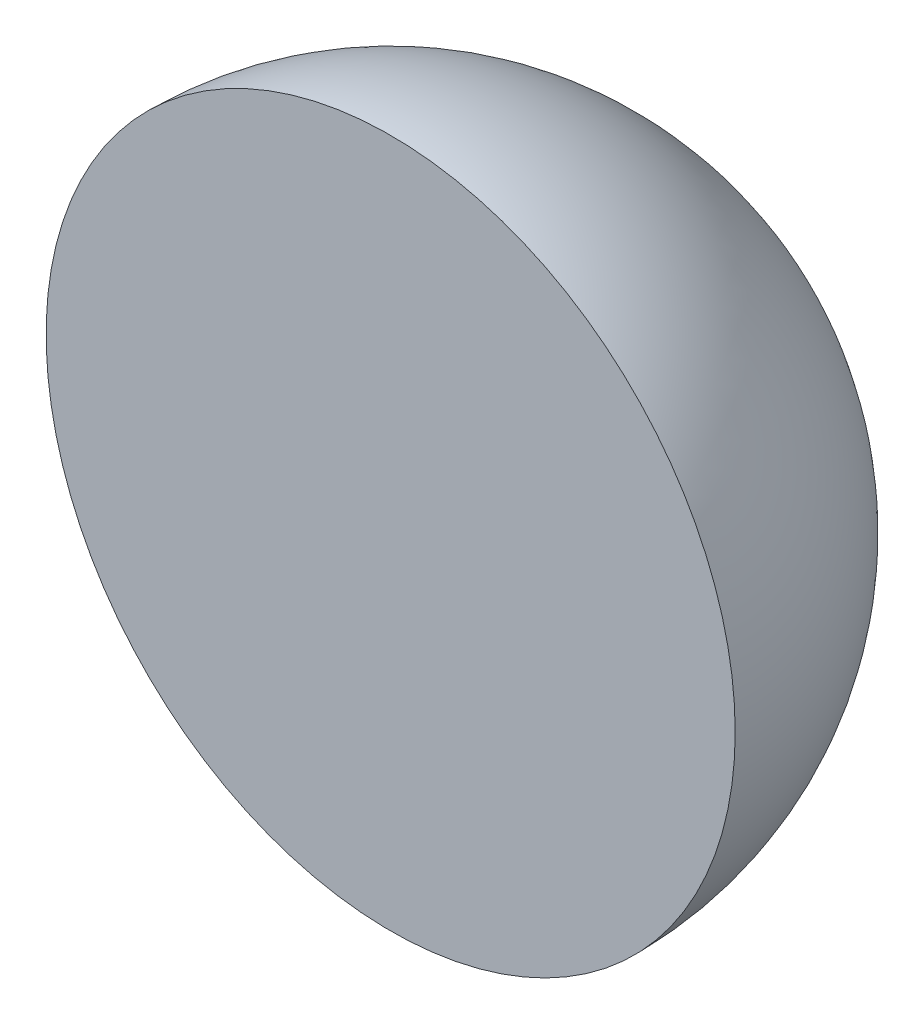
SolidWorks part; units mm, degrees
ref_plane "Front Plane" through (0, 0, 0) normal (0, 0, 1) x (1, 0, 0)
ref_plane "Top Plane" through (0, 0, 0) normal (0, 1, 0) x (1, 0, 0)
ref_plane "Right Plane" through (0, 0, 0) normal (1, 0, 0) x (0, 0, -1)
sketch "Sketch1" plane through (0, 0, 0) normal (0, 0, 1) x (1, 0, 0)
  line L0 (0.5, 0) -> (-0.5, 0)
  arc A0 (0.5, 0) -> (-0.5, 0) centre (0, 0) ccw
  dimension "D1" = 1
revolve "Revolve1" add sketch "Sketch1" angle 180 about L0
